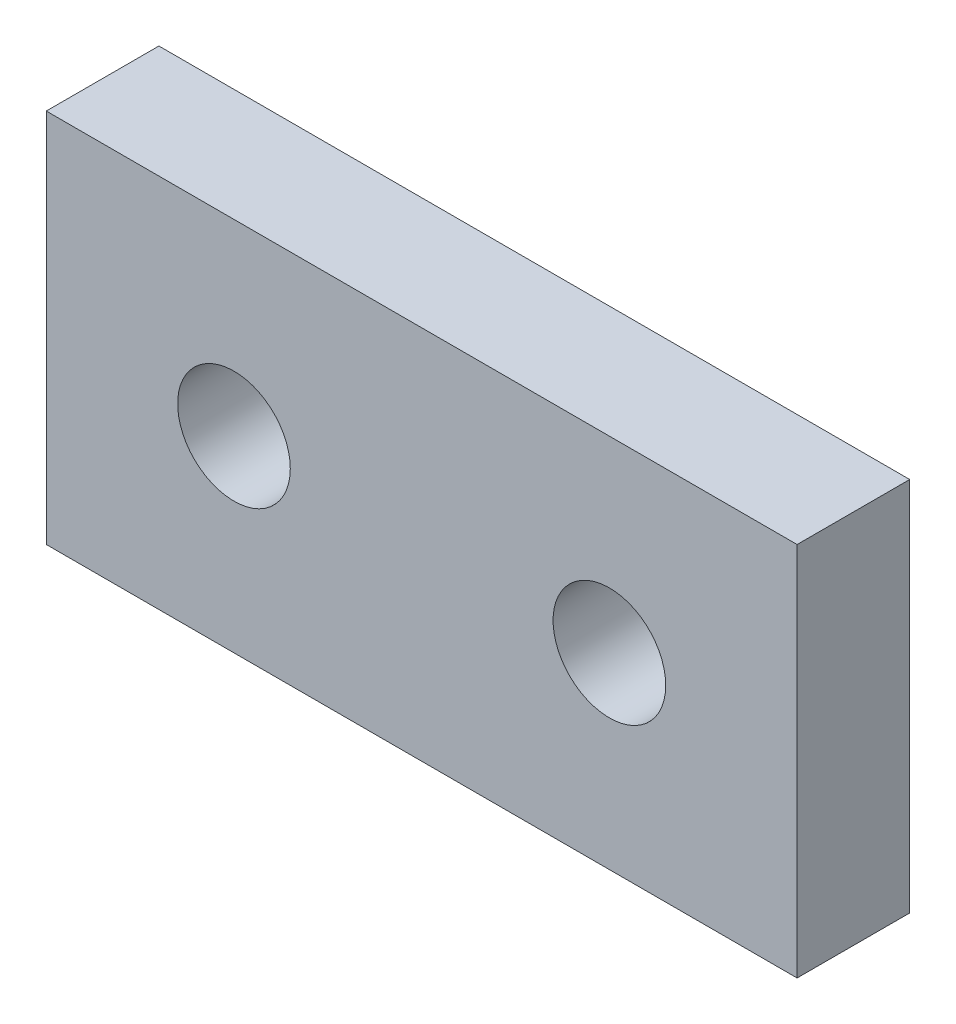
SolidWorks part; units mm, degrees
material "Wrought Stainless Steel"
ref_plane "Front Plane" through (0, 0, 0) normal (0, 0, 1) x (1, 0, 0)
ref_plane "Top Plane" through (0, 0, 0) normal (0, 1, 0) x (1, 0, 0)
ref_plane "Right Plane" through (0, 0, 0) normal (1, 0, 0) x (0, 0, -1)
sketch "Sketch1" plane through (0, 0, 0) normal (0, 0, 1) x (1, 0, 0)
  line L0 (-1000, 0) -> (49000, 0) construction
  line L1 (-10, -5) -> (10, -5)
  line L2 (-10, -5) -> (-10, 5)
  line L3 (-10, 5) -> (10, 5)
  line L4 (10, -5) -> (10, 5)
  line L5 (-10, -5) -> (10, 5) construction
  line L6 (-10, 5) -> (10, -5) construction
  circle A0 centre (-5, 0) radius 1.5
  circle A1 centre (5, 0) radius 1.5
  point P0 (0, 0)
  dimension "D3" = 3
  dimension "D1" = 20
  dimension "D2" = 10
  dimension "D4" = 5
  dimension "D5" = 5
extrude "Boss-Extrude1" add sketch "Sketch1" along normal blind 3
